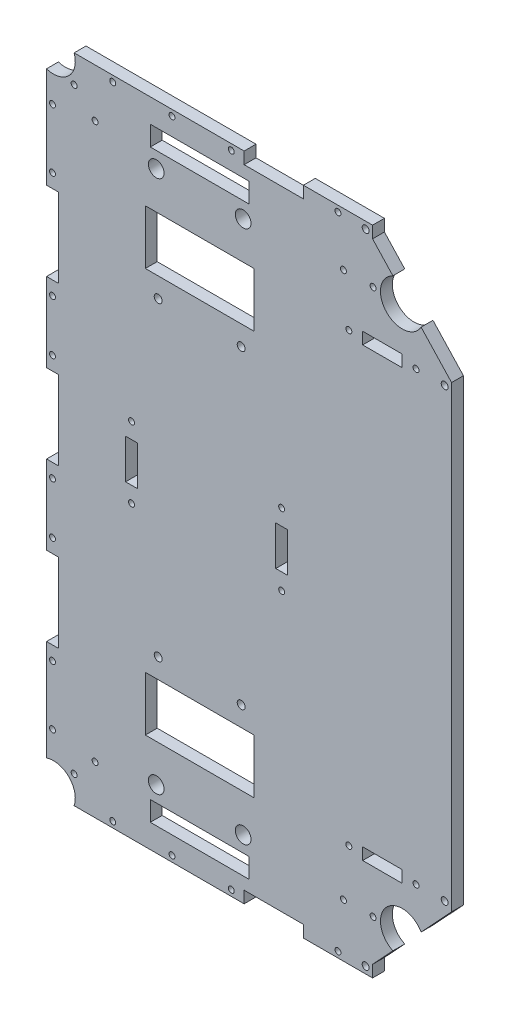
SolidWorks part; units mm, degrees
ref_plane "Plan de face" through (0, 0, 0) normal (0, 0, 1) x (1, 0, 0)
ref_plane "Plan de dessus" through (0, 0, 0) normal (0, 1, 0) x (1, 0, 0)
ref_plane "Plan de droite" through (0, 0, 0) normal (1, 0, 0) x (0, 0, -1)
sketch "Esquisse1" plane through (0, 0, 0) normal (0, 0, 1) x (1, 0, 0)
  line L1 (0, 0) -> (-205, 0)
  line L2 (0, 0) -> (0, 330)
  line L3 (0, 330) -> (-205, 330)
  line L4 (-205, 0) -> (-205, 330)
  dimension "D1" = 330
  dimension "D2" = 205
extrude "Boss.-Extru.1" add sketch "Esquisse1" along normal blind 6
sketch "Esquisse2" plane through (0, 0, 6) normal (0, 0, 1) x (1, 0, 0)
  line L0 (-205, 0) -> (0, 0) construction
  line L2 (-205, 0) -> (-156, 49) construction
  line L9 (0, 330) -> (-205, 330) construction
  line L10 (-205, 330) -> (-205, 0) construction
  line L11 (0, 0) -> (0, 330) construction
  line L12 (-205, 165) -> (0, 165) construction
  line L20 (0, 330) -> (-205, 330) construction
  line L21 (-205, 0) -> (0, 0) construction
  line L23 (0, 0) -> (0, 330) construction
  line L32 (-25, 275) -> (-45, 275)
  line L33 (-25, 275) -> (-25, 281)
  line L34 (-25, 281) -> (-45, 281)
  line L35 (-45, 275) -> (-45, 281)
  line L36 (-25, 49) -> (-45, 49)
  line L37 (-25, 49) -> (-25, 55)
  line L38 (-25, 55) -> (-45, 55)
  line L39 (-45, 49) -> (-45, 55)
  circle A0 centre (-201.4645, 3.5355) radius 11
  circle A1 centre (-39.73, 303) radius 1.5
  circle A2 centre (-25, 303) radius 11
  circle A3 centre (-191.0488, 13.9512) radius 1.5
  circle A4 centre (-180.4422, 24.5578) radius 1.5
  circle A5 centre (-25, 27) radius 11
  circle A6 centre (-201.4645, 326.4645) radius 11
  circle A7 centre (-191.0488, 316.0488) radius 1.5
  circle A8 centre (-180.4422, 305.4422) radius 1.5
  circle A9 centre (-54.73, 303) radius 1.5
  circle A14 centre (-39.73, 27) radius 1.5
  circle A15 centre (-54.73, 27) radius 1.5
  dimension "D10" = 14.73
  dimension "D13" = 22
  dimension "D16" = 15
  dimension "D18" = 22
  dimension "D17" = 27
  dimension "D21" = 25
  dimension "D14" = 15
  dimension "D26" = 25
  dimension "D39" = 3
  dimension "D40" = 3
  dimension "D43" = 3
  dimension "D44" = 3
  dimension "D8" = 3
  dimension "D9" = 135
  dimension "D6" = 22
  dimension "D7" = 3
  dimension "D11" = 5
  dimension "D22" = 27
  dimension "D25" = 20
  dimension "D27" = 25
  dimension "D28" = 27
  dimension "D29" = 49
  dimension "D30" = 6
  dimension "D38" = 14.73
  dimension "D42" = 27
  dimension "D45" = 15
  dimension "D46" = 14.73
  dimension "D47" = 27
  dimension "D48" = 27
  dimension "D49" = 20
  dimension "D50" = 6
  dimension "D51" = 25
  dimension "D52" = 49
extrude "roulement + encoche interne" cut sketch "Esquisse2" against normal through all
sketch "Esquisse3" plane through (0, 0, 6) normal (0, 0, 1) x (1, 0, 0)
  line L0 (0, 330) -> (-40, 330)
  line L1 (-40, 330) -> (-40, 324)
  line L2 (-40, 324) -> (0, 281)
  line L3 (-191.0481, 0) -> (0, 0) construction
  line L4 (0, 281) -> (0, 330)
  line L5 (-40, 0) -> (-40, 6)
  line L6 (-40, 6) -> (0, 49)
  line L8 (-205, 316.0481) -> (-205, 13.9519) construction
  line L9 (0, 0) -> (-40, 0)
  line L10 (0, 0) -> (0, 330) construction
  line L11 (0, 330) -> (-191.0481, 330) construction
  line L12 (-75, 0) -> (-105, 0)
  line L13 (-75, 0) -> (-75, 6)
  line L14 (-205, 145) -> (-199, 145)
  line L15 (-205, 65) -> (-199, 65)
  line L16 (-205, 65) -> (-205, 105)
  line L17 (-205, 105) -> (-199, 105)
  line L18 (-199, 65) -> (-199, 105)
  line L19 (-205, 145) -> (-205, 185)
  line L20 (-205, 185) -> (-199, 185)
  line L21 (-75, 6) -> (-105, 6)
  line L22 (-105, 0) -> (-105, 6)
  line L23 (-75, 330) -> (-105, 330)
  line L24 (-75, 330) -> (-75, 324)
  line L25 (-75, 324) -> (-105, 324)
  line L26 (-105, 330) -> (-105, 324)
  line L28 (-199, 145) -> (-199, 185)
  line L29 (-205, 225) -> (-199, 225)
  line L30 (-205, 225) -> (-205, 265)
  line L31 (-205, 265) -> (-199, 265)
  line L32 (-199, 225) -> (-199, 265)
  line L33 (0, 49) -> (0, 0)
  dimension "D3" = 49
  dimension "D4" = 6
  dimension "D5" = 40
  dimension "D6" = 30
  dimension "D7" = 40
  dimension "D8" = 6
  dimension "D9" = 40
  dimension "D10" = 6
  dimension "D11" = 40
  dimension "D12" = 40
  dimension "D13" = 40
  dimension "D14" = 6
  dimension "D15" = 75
  dimension "D16" = 65
  dimension "D17" = 6
  dimension "D18" = 30
  dimension "D19" = 75
  dimension "D20" = 6
  dimension "D21" = 6
  dimension "D23" = 40
  dimension "D24" = 49
extrude "Enlèv. mat encoche" cut sketch "Esquisse3" against normal through all
sketch "Esquisse6" plane through (0, 0, 6) normal (0, 0, 1) x (1, 0, 0)
  line L0 (-199, 165) -> (0, 165) construction
  line L1 (-155, 281) -> (-100, 281)
  line L2 (-155, 281) -> (-155, 253.5)
  line L3 (-155, 253.5) -> (-100, 253.5)
  line L4 (-100, 281) -> (-100, 253.5)
  line L5 (-199, 145) -> (-199, 185) construction
  line L6 (0, 49) -> (0, 281) construction
  line L7 (-205, 316.0481) -> (-205, 265) construction
  line L8 (-127.5, 250.9395) -> (-127.5, -49749.0605) construction
  line L10 (-152.5, 318) -> (-102.5, 318)
  line L11 (-152.5, 318) -> (-152.5, 308)
  line L12 (-152.5, 308) -> (-102.5, 308)
  line L13 (-102.5, 318) -> (-102.5, 308)
  line L14 (-102.5, 12) -> (-102.5, 22)
  line L15 (-152.5, 22) -> (-102.5, 22)
  line L16 (-152.5, 12) -> (-152.5, 22)
  line L17 (-152.5, 12) -> (-102.5, 12)
  line L18 (-100, 49) -> (-100, 76.5)
  line L19 (-155, 76.5) -> (-100, 76.5)
  line L20 (-155, 49) -> (-155, 76.5)
  line L21 (-155, 49) -> (-100, 49)
  line L22 (-165, 155) -> (-159, 155)
  line L23 (-165, 155) -> (-165, 175)
  line L24 (-165, 175) -> (-159, 175)
  line L25 (-159, 155) -> (-159, 175)
  line L26 (-89, 155) -> (-83, 155)
  line L27 (-89, 155) -> (-89, 175)
  line L28 (-89, 175) -> (-83, 175)
  line L29 (-83, 155) -> (-83, 175)
  circle A0 centre (-148.5, 243.5) radius 2
  circle A1 centre (-106.5, 243.5) radius 2
  circle A2 centre (-149.5, 300) radius 3.975
  circle A3 centre (-105.5, 300) radius 3.975
  circle A4 centre (-105.5, 30) radius 3.975
  circle A5 centre (-149.5, 30) radius 3.975
  circle A6 centre (-106.5, 86.5) radius 2
  circle A7 centre (-148.5, 86.5) radius 2
  point P18 (-127.5, 281)
  point P19 (-127.5, 253.5)
  dimension "D4" = 4
  dimension "D5" = 78.5
  dimension "D6" = 7.95
  dimension "D1" = 55
  dimension "D2" = 27.5
  dimension "D3" = 50
  dimension "D7" = 42
  dimension "D8" = 10
  dimension "D9" = 27
  dimension "D10" = 44
  dimension "D11" = 8
  dimension "D12" = 25
  dimension "D13" = 10
  dimension "D14" = 50
  dimension "D15" = 20
  dimension "D16" = 6
  dimension "D17" = 10
  dimension "D18" = 34
  dimension "D19" = 6
  dimension "D20" = 20
  dimension "D21" = 10
  dimension "D22" = 70
extrude "bloc moteur" cut sketch "Esquisse6" against normal through all
sketch "Esquisse7" plane through (0, 0, 6) normal (0, 0, 1) x (1, 0, 0)
  line L0 (-191.0481, 0) -> (-105, 0) construction
  line L1 (-205, 65) -> (-205, 13.9519) construction
  line L2 (-40, 330) -> (-40, 324) construction
  line L3 (-75, 0) -> (-40, 0) construction
  line L4 (-165, 155) -> (-159, 155) construction
  line L5 (-40, 330) -> (-75, 330) construction
  line L6 (-205, 145) -> (-205, 105) construction
  line L7 (-199, 105) -> (-205, 105) construction
  line L8 (-205, 145) -> (-199, 145) construction
  line L9 (-205, 225) -> (-205, 185) construction
  line L10 (-199, 185) -> (-205, 185) construction
  line L11 (-205, 225) -> (-199, 225) construction
  line L12 (-205, 316.0481) -> (-205, 265) construction
  line L13 (-199, 265) -> (-205, 265) construction
  line L14 (-105, 330) -> (-191.0481, 330) construction
  line L15 (-205, 65) -> (-205, 13.9519) construction
  line L16 (-45, 55) -> (-45, 49) construction
  line L17 (-45, 49) -> (-25, 49) construction
  line L18 (-25, 49) -> (-25, 55) construction
  line L19 (-75, 324) -> (-75, 330) construction
  line L20 (-40, 330) -> (-75, 330) construction
  line L21 (-205, 65) -> (-199, 65) construction
  line L22 (-25, 281) -> (-45, 281) construction
  line L23 (-45, 281) -> (-45, 275) construction
  line L24 (-45, 275) -> (-25, 275) construction
  line L25 (-25, 275) -> (-25, 281) construction
  line L26 (0, 49) -> (0, 281) construction
  line L27 (-45, 275) -> (-25, 275) construction
  line L28 (-45, 49) -> (-25, 49) construction
  line L29 (-75, 0) -> (-40, 0) construction
  line L30 (-40, 6) -> (-40, 0) construction
  line L31 (-75, 0) -> (-75, 6) construction
  line L32 (-159, 155) -> (-159, 175) construction
  line L33 (-205, 316.0481) -> (-205, 265) construction
  line L34 (-159, 175) -> (-165, 175) construction
  line L35 (-83, 175) -> (-89, 175) construction
  line L36 (-83, 155) -> (-83, 175) construction
  line L37 (-89, 155) -> (-83, 155) construction
  circle A0 centre (-57.5, 3) radius 1.5
  circle A1 centre (-171.5042, 3) radius 1.5
  circle A2 centre (-111.5042, 3) radius 1.5
  circle A3 centre (-202, 58) radius 1.5
  circle A4 centre (-202, 272) radius 1.5
  circle A5 centre (-57.5, 327) radius 1.5
  circle A6 centre (-171.5, 327) radius 1.5
  circle A7 centre (-18, 52) radius 1.5
  circle A8 centre (-52, 52) radius 1.5
  circle A9 centre (-18, 278) radius 1.5
  circle A10 centre (-52, 278) radius 1.5
  circle A11 centre (-202, 112) radius 1.5
  circle A12 centre (-202, 138) radius 1.5
  circle A13 centre (-162, 147) radius 1.505
  circle A14 centre (-141.5, 327) radius 1.5
  circle A15 centre (-202, 192) radius 1.5
  circle A16 centre (-202, 218) radius 1.5
  circle A17 centre (-162, 183) radius 1.505
  circle A18 centre (-141.5042, 3) radius 1.5
  circle A19 centre (-111.5, 327) radius 1.5
  circle A20 centre (-202, 302) radius 1.5
  circle A21 centre (-202, 28) radius 1.5
  circle A22 centre (-43.5, 326.5) radius 1.75
  circle A23 centre (-3.5, 278) radius 1.75
  circle A24 centre (-3.5, 52) radius 1.75
  circle A25 centre (-43.5, 3.5) radius 1.75
  circle A26 centre (-86, 146.73) radius 1.5
  circle A27 centre (-86, 183) radius 1.505
  point P71 (-25, 52)
  dimension "D1" = 3
  dimension "D2" = 3
  dimension "D6" = 3
  dimension "D7" = 3
  dimension "D8" = 3
  dimension "D9" = 30
  dimension "D10" = 3
  dimension "D11" = 3
  dimension "D13" = 33.4958
  dimension "D14" = 3
  dimension "D15" = 30
  dimension "D16" = 3
  dimension "D17" = 3
  dimension "D18" = 7
  dimension "D19" = 3
  dimension "D20" = 3
  dimension "D21" = 7
  dimension "D22" = 3
  dimension "D23" = 3
  dimension "D24" = 7
  dimension "D25" = 3
  dimension "D26" = 3
  dimension "D27" = 7
  dimension "D28" = 3
  dimension "D29" = 3
  dimension "D30" = 7
  dimension "D31" = 3
  dimension "D32" = 3
  dimension "D33" = 7
  dimension "D34" = 33.5
  dimension "D35" = 3.01
  dimension "D36" = 3.01
  dimension "D37" = 3
  dimension "D38" = 7
  dimension "D39" = 3
  dimension "D40" = 3
  dimension "D41" = 3
  dimension "D42" = 7
  dimension "D43" = 3
  dimension "D44" = 17.5
  dimension "D45" = 3
  dimension "D46" = 3
  dimension "D47" = 3
  dimension "D48" = 8
  dimension "D49" = 3
  dimension "D50" = 30
  dimension "D51" = 3
  dimension "D52" = 3
  dimension "D53" = 3
  dimension "D55" = 3
  dimension "D56" = 3
  dimension "D57" = 7
  dimension "D58" = 3
  dimension "D59" = 30
  dimension "D60" = 3
  dimension "D61" = 3
  dimension "D62" = 30
  dimension "D63" = 3
  dimension "D64" = 3
  dimension "D65" = 30
  dimension "D66" = 3
  dimension "D67" = 3.5
  dimension "D68" = 3.5
  dimension "D69" = 3.5
  dimension "D70" = 3.5
  dimension "D71" = 3.5
  dimension "D73" = 3.5
  dimension "D74" = 3.5
  dimension "D75" = 3
  dimension "D76" = 3.5
  dimension "D77" = 3.5
  dimension "D78" = 3.5
  dimension "D79" = 3
  dimension "D81" = 3
  dimension "D82" = 3.01
  dimension "D84" = 3
  dimension "D85" = 3
  dimension "D86" = 8.27
  dimension "D87" = 3
  dimension "D12" = 17.5
  dimension "D54" = 7
  dimension "D72" = 3
  dimension "D80" = 8
  dimension "D83" = 8
extrude "Enlèv. mat.-Extru.4" cut sketch "Esquisse7" against normal through all
sketch "Esquisse8" plane through (0, 0, 0) normal (0, 0, -1) x (-1, 0, 0)
  line L1 (199, 165) -> (0, 165) construction
  line L4 (199, 145) -> (199, 185) construction
  line L5 (0, 49) -> (0, 281) construction
  circle A1 centre (171.5, 327) radius 2.995
  circle A2 centre (202, 302) radius 2.995
  circle A3 centre (202, 272) radius 2.995
  circle A4 centre (202, 218) radius 2.995
  circle A5 centre (202, 192) radius 2.995
  circle A6 centre (141.5, 327) radius 2.995
  circle A7 centre (111.5, 327) radius 2.995
  circle A8 centre (57.5, 327) radius 2.995
  circle A9 centre (52, 278) radius 2.995
  circle A10 centre (18, 278) radius 2.995
  circle A11 centre (148.5, 243.5) radius 4
  circle A12 centre (106.5, 243.5) radius 4
  circle A13 centre (106.5, 86.5) radius 4
  circle A14 centre (148.5, 86.5) radius 4
  circle A15 centre (3.5, 278) radius 3.495
  circle A16 centre (52, 52) radius 2.995
  circle A17 centre (18, 52) radius 2.995
  circle A18 centre (57.5, 3) radius 2.995
  circle A19 centre (111.5, 3) radius 2.995
  circle A20 centre (141.5, 3) radius 2.995
  circle A21 centre (171.5, 3) radius 2.995
  circle A23 centre (202, 28) radius 2.995
  circle A24 centre (202, 58) radius 2.995
  circle A25 centre (202, 112) radius 2.995
  circle A26 centre (202, 138) radius 2.995
  circle A27 centre (54.73, 303) radius 3
  circle A28 centre (39.73, 303) radius 3
  circle A29 centre (39.73, 27) radius 3
  circle A30 centre (54.73, 27) radius 3
  circle A31 centre (180.4422, 305.4422) radius 3
  circle A32 centre (191.0488, 316.0488) radius 3
  circle A33 centre (191.0488, 13.9512) radius 3
  circle A34 centre (180.4422, 24.5578) radius 3
  circle A35 centre (43.5, 326.5) radius 3.495
  circle A36 centre (43.5, 3.5) radius 3.495
  circle A37 centre (3.5, 52) radius 3.495
  dimension "D1" = 5.99
  dimension "D2" = 5.99
  dimension "D3" = 5.99
  dimension "D4" = 5.99
  dimension "D6" = 5.99
  dimension "D7" = 5.99
  dimension "D8" = 5.99
  dimension "D9" = 5.99
  dimension "D10" = 5.99
  dimension "D11" = 5.99
  dimension "D12" = 8
  dimension "D13" = 8
  dimension "D14" = 6
  dimension "D15" = 6
  dimension "D16" = 6
  dimension "D17" = 6
  dimension "D18" = 6.99
  dimension "D19" = 6.99
  dimension "D20" = 6.99
  dimension "D21" = 6.99
extrude "Enlèv. mat.-Extru.7" cut sketch "Esquisse8" against normal blind 3
